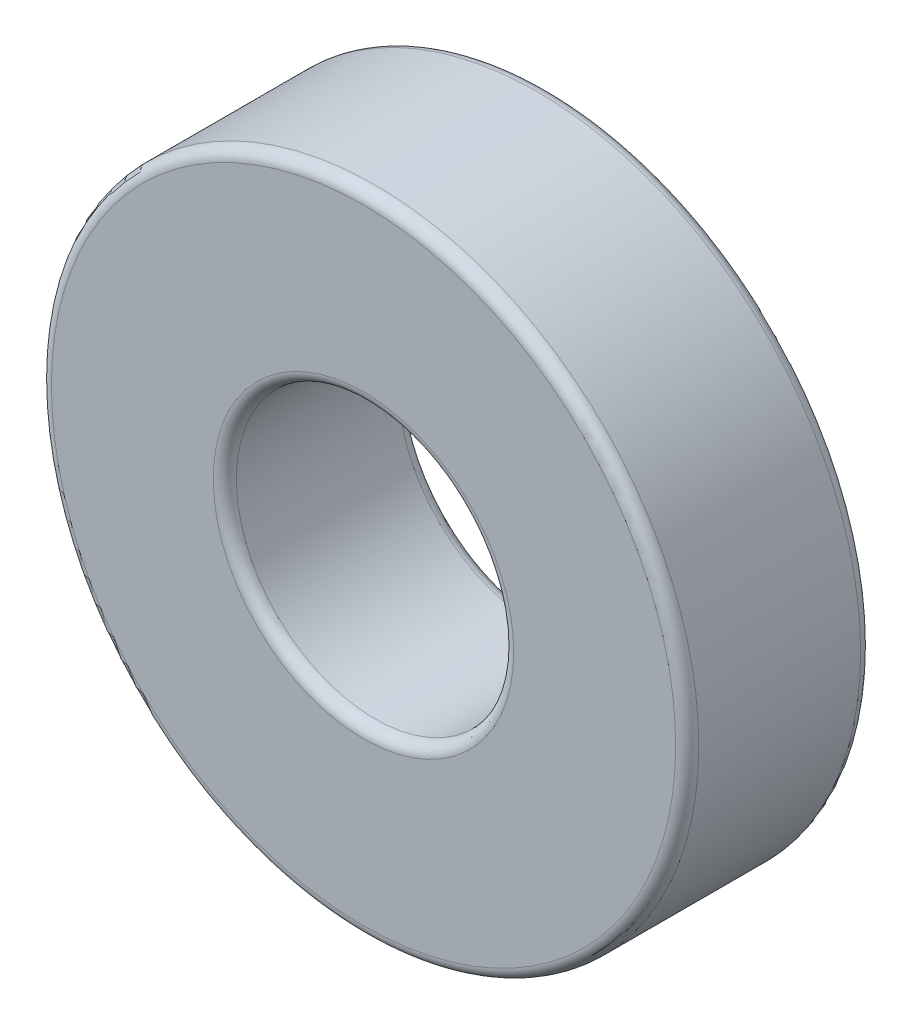
SolidWorks part; units mm, degrees
ref_plane "Front" through (0, 0, 0) normal (0, 0, 1) x (1, 0, 0)
ref_plane "Top" through (0, 0, 0) normal (0, 1, 0) x (1, 0, 0)
ref_plane "Right" through (0, 0, 0) normal (1, 0, 0) x (0, 0, -1)
sketch "Esquisse1" plane through (0, 0, 0) normal (0, 0, 1) x (1, 0, 0)
  circle A0 centre (0, 0) radius 6
  circle A1 centre (0, 0) radius 14
  dimension "D1" = 12
  dimension "D2" = 28
extrude "Boss.-Extru.1" add sketch "Esquisse1" along normal blind 8
fillet "Congé1" radius 0.5 4 edges at (6, 0, 0) (14, 0, 0) (6, 0, 8) (14, 0, 8)
